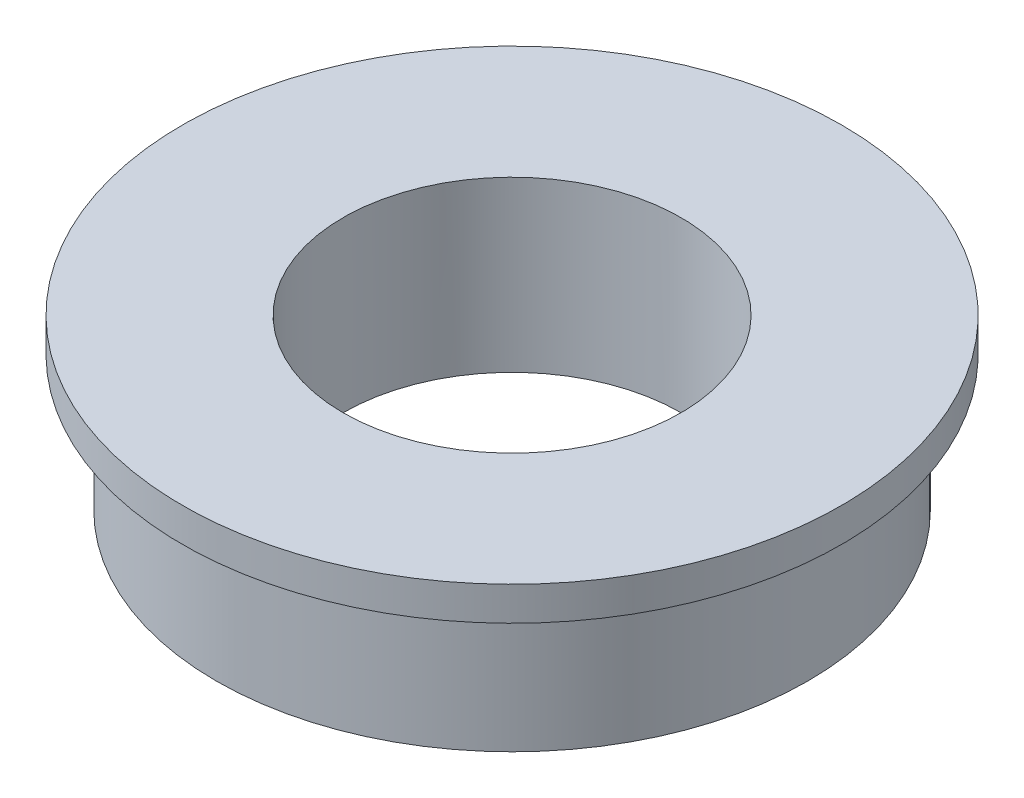
SolidWorks part; units mm, degrees
ref_plane "前视基准面" through (0, 0, 0) normal (0, 0, 1) x (1, 0, 0)
ref_plane "上视基准面" through (0, 0, 0) normal (0, 1, 0) x (1, 0, 0)
ref_plane "右视基准面" through (0, 0, 0) normal (1, 0, 0) x (0, 0, -1)
other "Configuration Table"
sketch "草图1" plane through (0, 0, 0) normal (0, 0, 1) x (1, 0, 0)
  line L0 (0, 0) -> (0, 6.731) construction
  line L1 (0, 4) -> (7.8, 4)
  line L2 (7.8, 4) -> (7.8, 3.2)
  line L3 (7.8, 3.2) -> (7, 3.2)
  line L4 (7, 3.2) -> (7, 0)
  line L5 (7, 0) -> (0, 0)
  line L6 (0, 4) -> (0, 0)
  dimension "D1" = 15.6
  dimension "D2" = 14
  dimension "D3" = 0.8
  dimension "D4" = 4
revolve "旋转1" add sketch "草图1" angle 360 about L0
sketch "草图2" plane through (0, 4, 0) normal (0, 1, 0) x (1, 0, 0)
  circle A0 centre (0, 0) radius 4
  dimension "D1" = 8
extrude "切除-拉伸1" cut sketch "草图2" against normal up to next
